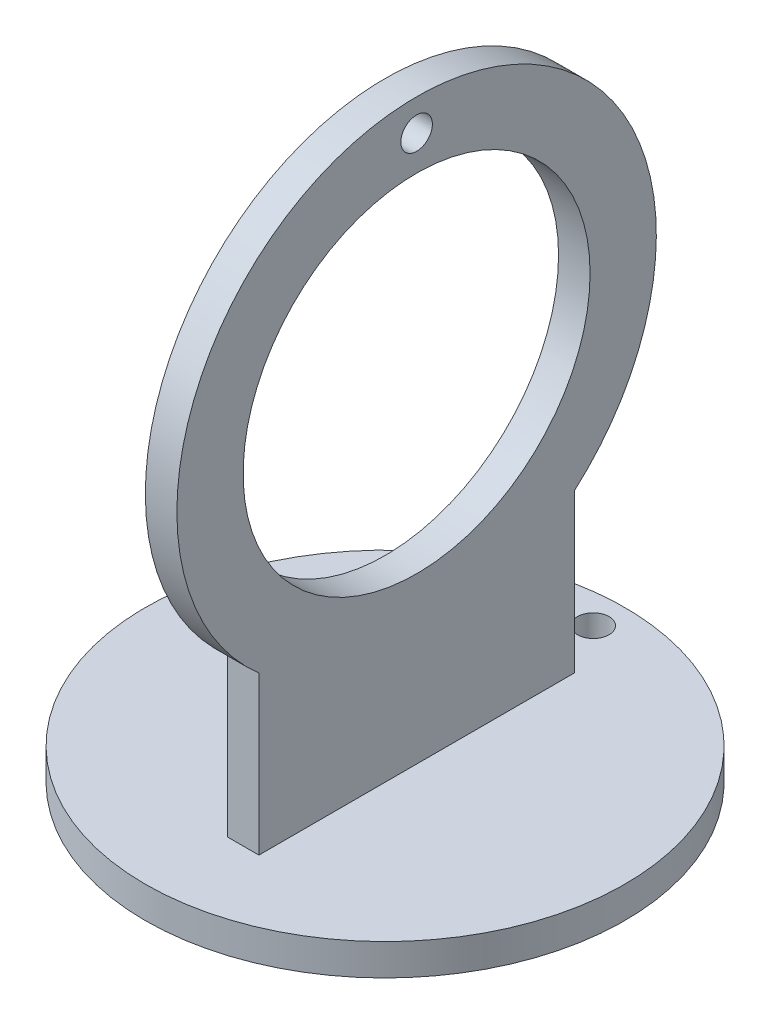
SolidWorks part; units mm, degrees
ref_plane "前视基准面" through (0, 0, 0) normal (0, 0, 1) x (1, 0, 0)
ref_plane "上视基准面" through (0, 0, 0) normal (0, 1, 0) x (1, 0, 0)
ref_plane "右视基准面" through (0, 0, 0) normal (1, 0, 0) x (0, 0, -1)
other "Configuration Table"
sketch "草图1" plane through (0, 0, 0) normal (0, 1, 0) x (1, 0, 0)
  circle A0 centre (0, 0) radius 38
  circle A1 centre (0, 0) radius 33 construction
  circle A2 centre (0, 33) radius 2.5
  dimension "D1" = 76
  dimension "D3" = 66
  dimension "D4" = 5
extrude "凸台-拉伸1" add sketch "草图1" along normal blind 5
ref_plane "基准面1" through (0, 0, 0) normal (1, 0, 0) x (0, 0, -1)
sketch "草图5" plane through (0, 0, 0) normal (1, 0, 0) x (0, 0, -1)
  line L0 (0, 17.5) -> (0, 0) construction
  line L1 (-25, 30) -> (25, 30) construction
  line L2 (-25, 30) -> (-25, 5)
  line L3 (-25, 5) -> (25, 5)
  line L4 (25, 30) -> (25, 5)
  line L5 (-25, 30) -> (25, 5) construction
  line L6 (-25, 5) -> (25, 30) construction
  line L7 (38, 5) -> (-38, 5) construction
  line L8 (0, 58.6182) -> (0, 17.5) construction
  arc A0 (25, 30) -> (-25, 30) centre (0, 58.6182) ccw
  circle A1 centre (0, 58.6182) radius 33 construction
  circle A2 centre (0, 91.6182) radius 2.5
  point P0 (0, 17.5)
  dimension "D2" = 38
  dimension "D4" = 66
  dimension "D5" = 5
  dimension "D1" = 50
  dimension "D3" = 25
extrude "凸台-拉伸3" add sketch "草图5" along normal blind 5
sketch "草图6" plane through (5, 0, 0) normal (1, 0, 0) x (0, 0, -1)
  circle A0 centre (0, 58.6182) radius 27.5
  dimension "D1" = 55
extrude "切除-拉伸1" cut sketch "草图6" against normal up to next
